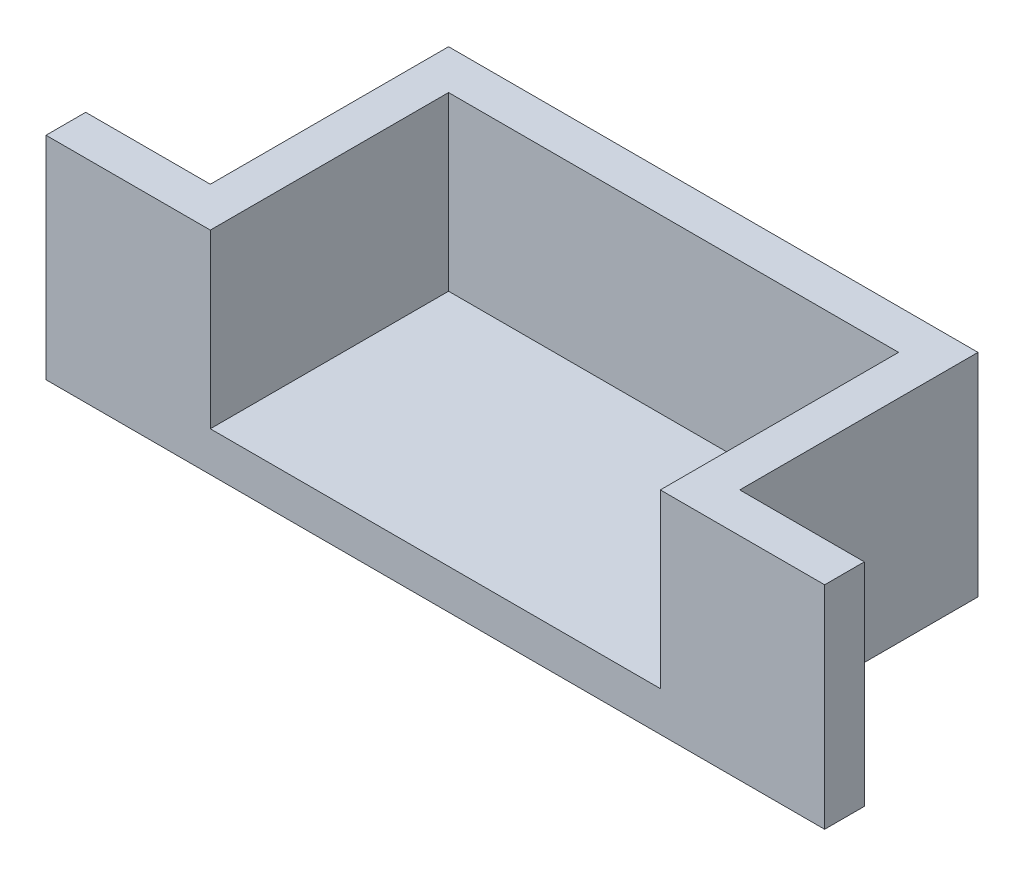
SolidWorks part; units mm, degrees
ref_plane "Front Plane" through (0, 0, 0) normal (0, 0, 1) x (1, 0, 0)
ref_plane "Top Plane" through (0, 0, 0) normal (0, 1, 0) x (1, 0, 0)
ref_plane "Right Plane" through (0, 0, 0) normal (1, 0, 0) x (0, 0, -1)
sketch "Sketch1" plane through (0, 0, 0) normal (0, 1, 0) x (1, 0, 0)
  line L0 (0, 0) -> (0, -15.5172) construction
  line L1 (-20, 7.9425) -> (20, 7.9425)
  line L2 (0, 7.9425) -> (0, 4.9425)
  line L3 (-20, 4.9425) -> (20, 4.9425)
  line L4 (20, 7.9425) -> (20, 4.9425)
  line L5 (20, 4.9425) -> (17, 4.9425)
  line L6 (20, 4.9425) -> (20, -10.0575)
  line L7 (20, -10.0575) -> (17, -10.0575)
  line L8 (17, 4.9425) -> (17, -10.0575)
  line L9 (17, -10.0575) -> (29.4138, -10.0575)
  line L10 (17, -10.0575) -> (17, -13.0575)
  line L11 (17, -13.0575) -> (29.4138, -13.0575)
  line L12 (29.4138, -10.0575) -> (29.4138, -13.0575)
  line L13 (-17, -13.0575) -> (-29.4138, -13.0575)
  line L14 (-29.4138, -10.0575) -> (-29.4138, -13.0575)
  line L15 (-17, -10.0575) -> (-29.4138, -10.0575)
  line L16 (-17, -10.0575) -> (-17, -13.0575)
  line L17 (-20, -10.0575) -> (-17, -10.0575)
  line L18 (-17, 4.9425) -> (-17, -10.0575)
  line L19 (-20, 4.9425) -> (-17, 4.9425)
  line L20 (-20, 4.9425) -> (-20, -10.0575)
  line L21 (-20, 7.9425) -> (-20, 4.9425)
  dimension "D1" = 20
  dimension "D2" = 3
  dimension "D3" = 3
  dimension "D4" = 3
  dimension "D5" = 18
extrude "Boss-Extrude1" add sketch "Sketch1" along normal blind 16 contours L3 L20 L15 L18 | L16 L15 L14 L13 | L1 L21 L3 L2 | L4 L1 L2 L3 | L3 L8 L7 L6 | L12 L9 L7 L10 L11
sketch "Sketch2" plane through (0, 0, 0) normal (0, 1, 0) x (1, 0, 0)
  line L1 (-17, 4.9425) -> (17, 4.9425)
  line L2 (-17, 4.9425) -> (-17, -13.0575)
  line L3 (-17, -13.0575) -> (17, -13.0575)
  line L4 (17, 4.9425) -> (17, -13.0575)
extrude "Boss-Extrude2" add sketch "Sketch2" along normal blind 3
